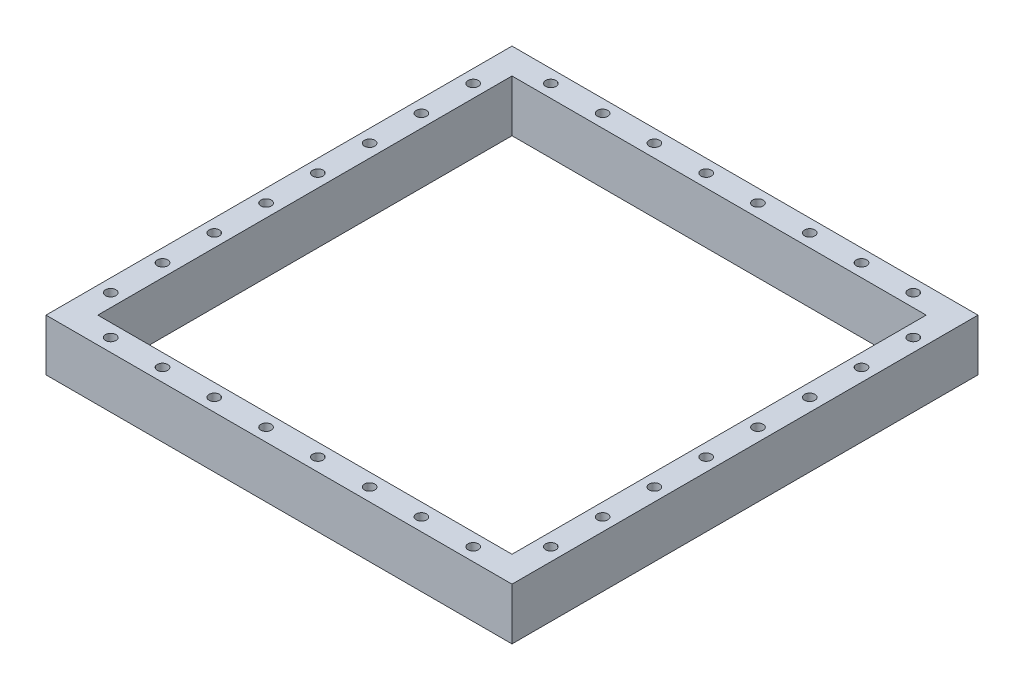
SolidWorks part; units mm, degrees
ref_plane "Front Plane" through (0, 0, 0) normal (0, 0, 1) x (1, 0, 0)
ref_plane "Top Plane" through (0, 0, 0) normal (0, 1, 0) x (1, 0, 0)
ref_plane "Right Plane" through (0, 0, 0) normal (1, 0, 0) x (0, 0, -1)
sketch "Sketch1" plane through (0, 0, 0) normal (0, 1, 0) x (1, 0, 0)
  line L1 (12.7, -12.7) -> (215.9, -12.7)
  line L2 (12.7, -12.7) -> (12.7, -215.9)
  line L3 (12.7, -215.9) -> (215.9, -215.9)
  line L4 (215.9, -12.7) -> (215.9, -215.9)
  line L7 (0, 0) -> (228.6, 0)
  line L8 (0, 0) -> (0, -228.6)
  line L9 (0, -228.6) -> (228.6, -228.6)
  line L10 (228.6, 0) -> (228.6, -228.6)
  point P0 (0, 0)
  point P6 (0, 0)
  dimension "D1" = 12.7
  dimension "D2" = 12.7
  dimension "D3" = 12.7
  dimension "D4" = 12.7
  dimension "D5" = 228.6
  dimension "D6" = 228.6
extrude "Boss-Extrude1" add sketch "Sketch1" along normal blind 25.4
hole_wizard "Tap Drill for 1/4-20 Tap1" positions "Sketch2" profile "Sketch3" hole size "1/4-20" standard "ANSI Inch"
sketch "Sketch2" plane through (0, 25.4, 0) normal (0, 1, 0) x (1, 0, 0)
  line L0 (114.3, 0) -> (114.3, -12.7) construction
  line L1 (228.6, 0) -> (0, 0) construction
  line L2 (215.9, -12.7) -> (12.7, -12.7) construction
  line L4 (0, -6.35) -> (228.6, -6.35) construction
  line L5 (0, 0) -> (0, -228.6) construction
  line L6 (228.6, -228.6) -> (228.6, 0) construction
  line L8 (12.7, -114.3) -> (0, -114.3) construction
  line L9 (12.7, -12.7) -> (12.7, -215.9) construction
  line L11 (6.35, -114.3) -> (6.35, 0) construction
  line L13 (0, -228.6) -> (228.6, 0) construction
  point P0 (25.4, -6.35)
  point P21 (114.3, -6.35)
  point P27 (50.8, -6.35)
  point P28 (76.2, -6.35)
  point P29 (101.6, -6.35)
  point P30 (127, -6.35)
  point P31 (152.4, -6.35)
  point P32 (177.8, -6.35)
  point P33 (203.2, -6.35)
  point P45 (6.35, -25.4)
  point P53 (6.35, -50.8)
  point P54 (6.35, -76.2)
  point P55 (6.35, -101.6)
  point P56 (6.35, -127)
  point P57 (6.35, -152.4)
  point P58 (6.35, -177.8)
  point P59 (6.35, -203.2)
  point P66 (222.25, -25.4)
  point P67 (222.25, -50.8)
  point P68 (222.25, -76.2)
  point P69 (222.25, -101.6)
  point P70 (222.25, -127)
  point P71 (222.25, -152.4)
  point P72 (222.25, -177.8)
  point P73 (222.25, -203.2)
  point P74 (25.4, -222.25)
  point P75 (50.8, -222.25)
  point P76 (76.2, -222.25)
  point P77 (101.6, -222.25)
  point P78 (127, -222.25)
  point P79 (152.4, -222.25)
  point P80 (177.8, -222.25)
  point P81 (203.2, -222.25)
  dimension "D1" = 25.4
  dimension "D3" = 25.4
  dimension "D2" = 8
  dimension "D4" = 8
sketch "Sketch3" plane through (25.4, 25.4, 6.35) normal (1, 0, 0) x (0, 0, 1)
  line L0 (0, 0) -> (0, 14.2338)
  line L1 (0, 14.2338) -> (2.5527, 12.7)
  line L2 (2.5527, 12.7) -> (2.5527, 0)
  line L5 (2.5527, 0) -> (0, 0)
  line L10 (0, 14.2338) -> (-2.5527, 12.7) construction
  line L11 (0, -6.35) -> (0, 107.95) construction
  dimension "Hole Dia." = 5.1054
  dimension "Hole Depth" = 12.7
  dimension "Drill Angle" = 118
